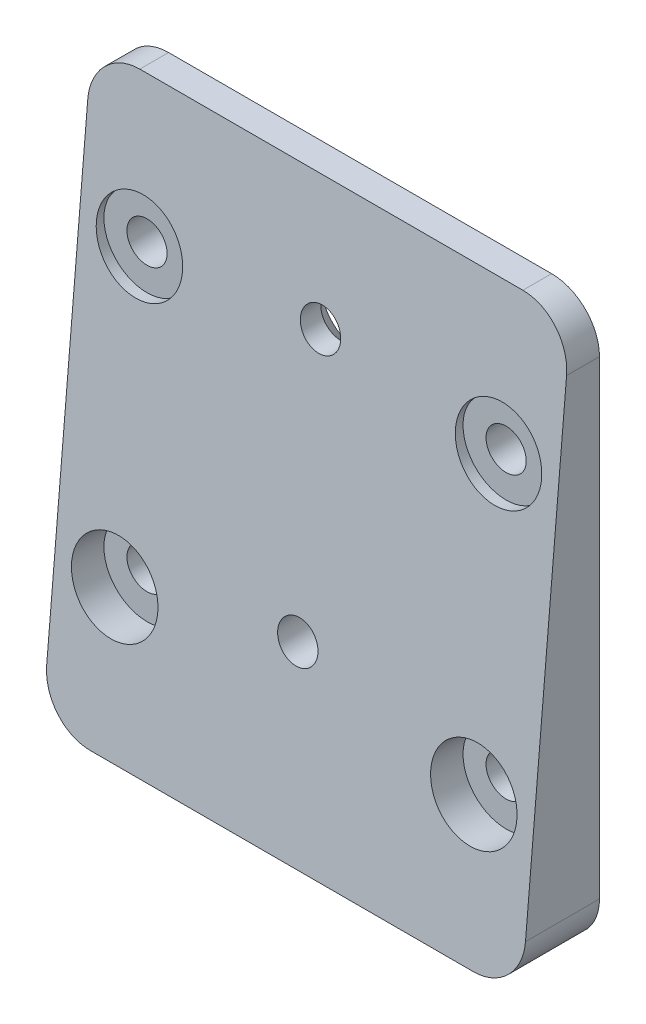
SolidWorks part; units mm, degrees
ref_plane "Piano frontale" through (0, 0, 0) normal (0, 0, 1) x (1, 0, 0)
ref_plane "Piano superiore" through (0, 0, 0) normal (0, 1, 0) x (1, 0, 0)
ref_plane "Piano destro" through (0, 0, 0) normal (1, 0, 0) x (0, 0, -1)
sketch "Schizzo1" plane through (0, 0, 0) normal (0, 0, 1) x (1, 0, 0)
  line L0 (0, 71.8474) -> (25, 71.8474)
  line L2 (25, 71.8474) -> (25, 12.8019)
  line L3 (25, 12.8019) -> (0, 12.8019)
  line L5 (0, 12.8019) -> (0, 71.8474) construction
  line L6 (12.5, 71.8474) -> (25, 42.3246) construction
  line L7 (25, 42.3246) -> (12.5, 12.8019) construction
  line L8 (-25, 12.8019) -> (0, 12.8019)
  line L9 (-25, 71.8474) -> (-25, 12.8019)
  line L10 (0, 71.8474) -> (-25, 71.8474)
  circle A0 centre (18.75, 57.086) radius 2.1
  circle A1 centre (18.75, 27.5632) radius 2.1
  circle A2 centre (-18.75, 27.5632) radius 2.1
  circle A3 centre (-18.75, 57.086) radius 2.1
  circle A4 centre (0, 58.8947) radius 2.1
  circle A5 centre (0, 31.8036) radius 2.1
  point P23 (0, 0)
  dimension "D2" = 4.2
  dimension "D3" = 4.2
  dimension "D1" = 25
extrude "Estrusione-Estrusione1" add sketch "Schizzo1" along normal blind 3
chamfer "Smusso1" distance 2 angle 45 2 edges at (2.1, 31.8036, 0) (2.1, 58.8947, 0)
sketch "Schizzo2" plane through (25, 0, 0) normal (1, 0, 0) x (0, 0, -1)
  line L0 (-3, 71.8474) -> (-8.1658, 12.8019)
  line L1 (-8.1658, 12.8019) -> (-3, 12.8019)
  line L2 (-3, 12.8019) -> (-3, 71.8474) construction
  line L3 (-3, 71.8474) -> (-3, 12.8019)
  dimension "D1" = 5
extrude "Estrusione-Estrusione2" add sketch "Schizzo2" against normal up to surface (50 mm away) up to face at (-25, 42.3246, 1.5)
sketch "Schizzo3" plane through (0, 0, 3) normal (0, 0, -1) x (-1, 0, 0)
  circle A0 centre (18.75, 27.5632) radius 2.1 construction
  circle A1 centre (18.75, 57.086) radius 2.1 construction
  circle A2 centre (-18.75, 57.086) radius 2.1 construction
  circle A3 centre (-18.75, 27.5632) radius 2.1 construction
  circle A4 centre (0, 31.8036) radius 2.1 construction
  circle A5 centre (0, 58.8947) radius 2.1 construction
  circle A6 centre (18.75, 27.5632) radius 2.1
  circle A7 centre (18.75, 57.086) radius 2.1
  circle A8 centre (-18.75, 57.086) radius 2.1
  circle A9 centre (-18.75, 27.5632) radius 2.1
  circle A10 centre (0, 31.8036) radius 2.1
  circle A11 centre (0, 58.8947) radius 2.1
extrude "Taglio-Estrusione1" cut sketch "Schizzo3" against normal blind 10
fillet "Raccordo1" radius 5 4 edges at (-25, 12.8019, 4.0829) (25, 12.8019, 4.0829) (-25, 71.8474, 1.5) (25, 71.8474, 1.5)
sketch "Schizzo5" plane through (0, 0.8062, 9.2153) normal (0, 0.0872, 0.9962) x (1, 0, 0)
  circle A0 centre (-18.75, 56.4948) radius 4.5
  circle A1 centre (18.75, 56.4948) radius 4.5
  circle A2 centre (18.75, 26.8592) radius 4.5
  circle A3 centre (-18.75, 26.8592) radius 4.5
  dimension "D1" = 9
extrude "Taglio-Estrusione3" cut sketch "Schizzo5" against normal offset from surface (1.1882 mm away) 3.5
equation "\"3.53.00mm\"=3"
